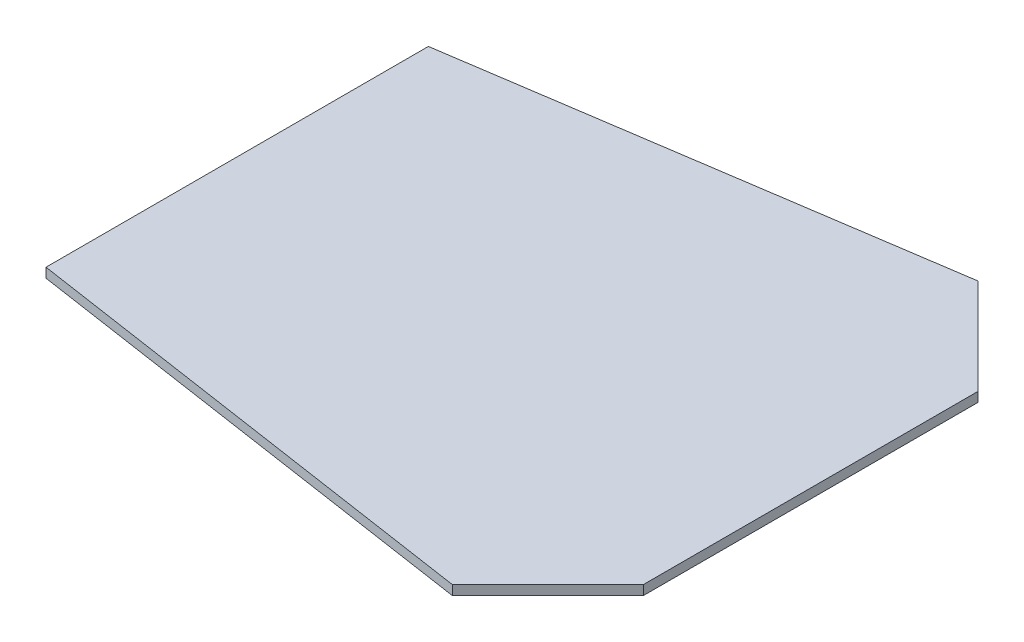
SolidWorks part; units mm, degrees
ref_plane "Front Plane" through (0, 0, 0) normal (0, 0, 1) x (1, 0, 0)
ref_plane "Top Plane" through (0, 0, 0) normal (0, 1, 0) x (1, 0, 0)
ref_plane "Right Plane" through (0, 0, 0) normal (1, 0, 0) x (0, 0, -1)
sketch "Sketch1" plane through (0, 0, 0) normal (0, 1, 0) x (1, 0, 0)
  line L0 (0, 200) -> (0, -200)
  line L2 (600, 175) -> (600, -175)
  line L3 (600, 175) -> (500, 275)
  line L12 (0, 200) -> (500, 275)
  line L13 (600, -175) -> (500, -275)
  line L14 (0, -200) -> (500, -275)
  dimension "D2" = 200
  dimension "D3" = 200
  dimension "D4" = 600
  dimension "D5" = 100
  dimension "D6" = 100
  dimension "D7" = 100
  dimension "D8" = 100
  dimension "D9" = 550
  dimension "D10" = 75
  dimension "D11" = 75
  dimension "D12" = 570.6356
extrude "Boss-Extrude1" add sketch "Sketch1" along normal blind 10
